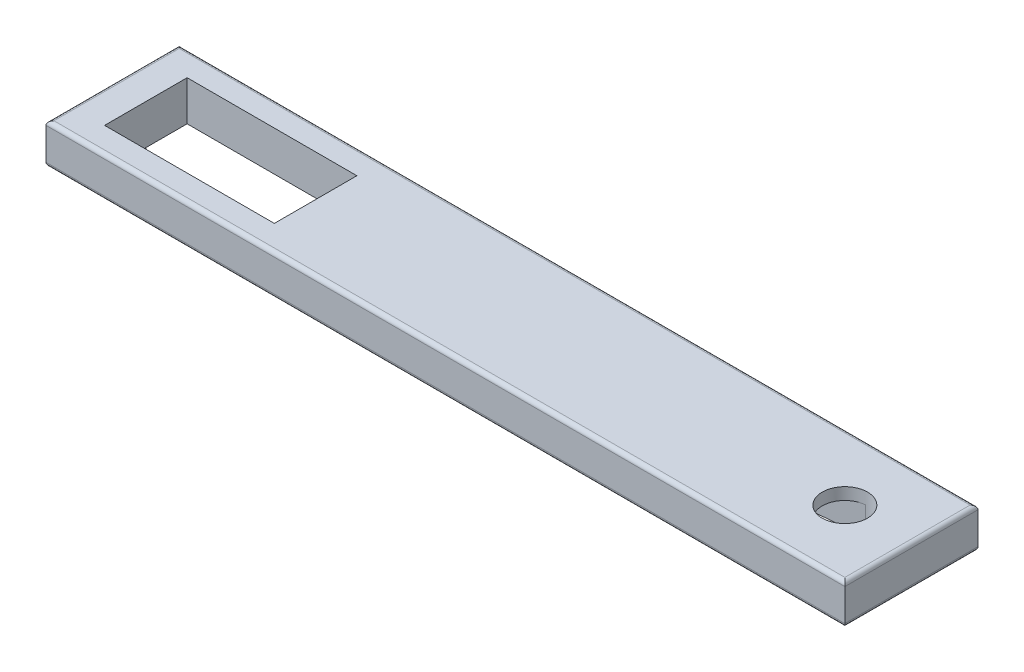
SolidWorks part; units mm, degrees
ref_plane "Front Plane" through (0, 0, 0) normal (0, 0, 1) x (1, 0, 0)
ref_plane "Top Plane" through (0, 0, 0) normal (0, 1, 0) x (1, 0, 0)
ref_plane "Right Plane" through (0, 0, 0) normal (1, 0, 0) x (0, 0, -1)
sketch "Sketch1" plane through (0, 0, 0) normal (0, 1, 0) x (1, 0, 0)
  line L0 (93.6749, 11.9421) -> (109.6947, 13.3863)
  line L1 (0, 0) -> (120, 0)
  line L2 (0, 0) -> (0, 20)
  line L3 (0, 20) -> (120, 20)
  line L4 (120, 0) -> (120, 20)
  line L5 (5, 16.2) -> (30.5, 16.2)
  line L6 (5, 16.2) -> (5, 3.8)
  line L7 (5, 3.8) -> (30.5, 3.8)
  line L8 (30.5, 16.2) -> (30.5, 3.8)
  line L9 (93.6749, 8.0579) -> (109.6947, 6.6137)
  arc A2 (109.6947, 6.6137) -> (109.6947, 13.3863) centre (110, 10) ccw
  arc A3 (93.6749, 11.9421) -> (93.6749, 8.0579) centre (93.85, 10) ccw
  point P9 (5, 10)
  point P10 (0, 10)
  point P16 (120, 10)
  dimension "D6" = 6.8
  dimension "D7" = 3.9
  dimension "D1" = 20
  dimension "D2" = 120
  dimension "D3" = 25.5
  dimension "D4" = 12.4
  dimension "D5" = 5
  dimension "D8" = 16.15
  dimension "D9" = 10
extrude "Boss-Extrude1" add sketch "Sketch1" along normal blind 6
sketch "Sketch3" plane through (0, 0, 0) normal (0, -1, 0) x (1, 0, 0)
  line L0 (0, -20) -> (0, 0) construction
  line L1 (4.25, -10) -> (31.25, -10) construction
  line L2 (5, -3.8) -> (30.5, -3.8) construction
  circle A0 centre (4.25, -10) radius 0.55
  circle A1 centre (31.25, -10) radius 0.55
  point P7 (0, -10)
  point P9 (17.75, -3.8)
  point P10 (17.75, -10)
  dimension "D1" = 1.1
  dimension "D2" = 1.1
  dimension "D3" = 27
extrude "Boss-Extrude2" add sketch "Sketch3" along normal blind 3
sketch "Sketch4" plane through (0, 6, 0) normal (0, 1, 0) x (1, 0, 0)
  line L0 (120, 20) -> (0, 20) construction
  line L1 (84, 20) -> (120, 20)
  line L2 (84, 20) -> (84, 0)
  line L3 (84, 0) -> (120, 0)
  line L4 (120, 20) -> (120, 0)
  dimension "D1" = 36
extrude "Boss-Extrude3" add sketch "Sketch4" against normal blind 1.8
sketch "Sketch5" plane through (0, 4.2, 0) normal (0, -1, 0) x (1, 0, 0)
  circle A0 centre (110, -10) radius 3.4
extrude "Cut-Extrude1" cut sketch "Sketch5" against normal blind 1.8
fillet "Fillet1" radius 0.6 8 edges at (0, 0, -10) (0, 6, -10) (120, 0, -10) (120, 6, -10) (60, 6, 0) (60, 0, 0) (60, 0, -20) (60, 6, -20)
